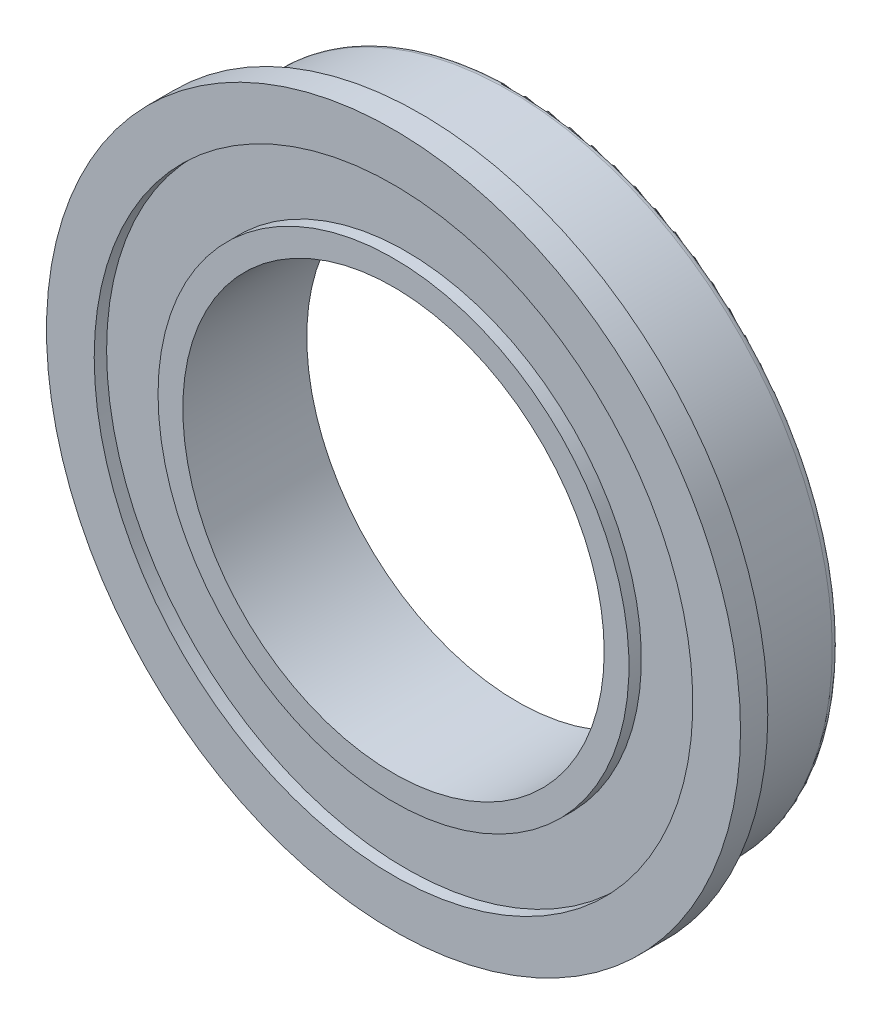
SolidWorks part; units mm, degrees
material "1.5714 (16NiCr4)"
ref_plane "前视基准面" through (0, 0, 0) normal (0, 0, 1) x (1, 0, 0)
ref_plane "上视基准面" through (0, 0, 0) normal (0, 1, 0) x (1, 0, 0)
ref_plane "右视基准面" through (0, 0, 0) normal (1, 0, 0) x (0, 0, -1)
sketch "草图1" plane through (0, 0, 0) normal (0, 0, 1) x (1, 0, 0)
  circle A0 centre (0, 0) radius 8.5
  circle A1 centre (0, 0) radius 13
extrude "凸台-拉伸1" add sketch "草图1" along normal blind 5
sketch "草图2" plane through (0, 0, 5) normal (0, 0, 1) x (1, 0, 0)
  circle A0 centre (0, 0) radius 14
  circle A1 centre (0, 0) radius 13
extrude "凸台-拉伸2" add sketch "草图2" against normal blind 1.1
fillet "圆角1" radius 0.3 1 edges at (13, 0, 0)
sketch "草图3" plane through (0, 0, 0) normal (1, 0, 0) x (0, 0, -1)
  line L0 (0, 0) -> (0, 16.148) construction
  line L1 (0, 0) -> (-6.5785, 0) construction
  line L3 (-5, 14) -> (-5, -14) construction
  line L4 (-5, 14) -> (-5, -14) construction
  line L5 (-0.5, 9.5) -> (0, 9.5)
  line L6 (-0.5, 9.5) -> (-0.5, 12.075)
  line L7 (-0.5, 12.075) -> (0, 12.075)
  line L8 (0, 9.5) -> (0, 12.075)
  line L9 (-0.5, 9.5) -> (0, 12.075) construction
  line L10 (-0.5, 12.075) -> (0, 9.5) construction
  line L16 (-4.5, 9.5) -> (-5, 9.5)
  line L17 (-4.5, 9.5) -> (-4.5, 12.075)
  line L18 (-4.5, 12.075) -> (-5, 12.075)
  line L19 (-5, 9.5) -> (-5, 12.075)
  line L20 (-4.5, 9.5) -> (-5, 12.075) construction
  line L21 (-4.5, 12.075) -> (-5, 9.5) construction
  point P6 (-0.25, 10.7875)
  point P11 (-4.75, 10.7875)
  dimension "D1" = 0.5
  dimension "D2" = 19
  dimension "D3" = 24.15
revolve "切除-旋转1" cut sketch "草图3" angle 360 about L1
move or copy body "实体-移动/复制1" [suppressed] bodies to move or copy 102
